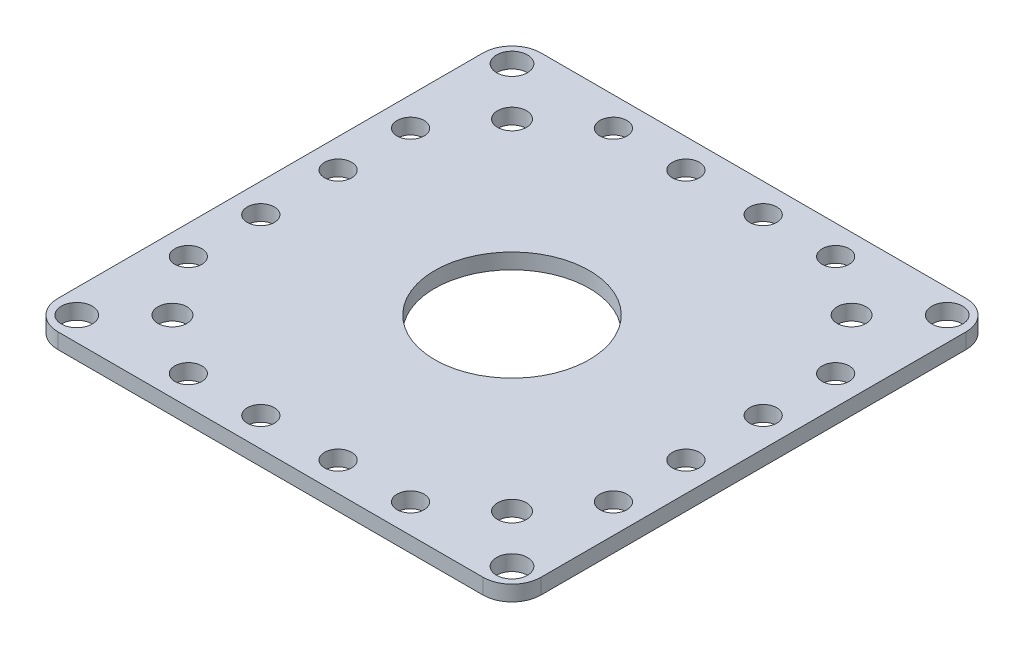
SolidWorks part; units mm, degrees
ref_plane "Front Plane" through (0, 0, 0) normal (0, 0, 1) x (1, 0, 0)
ref_plane "Top Plane" through (0, 0, 0) normal (0, 1, 0) x (1, 0, 0)
ref_plane "Right Plane" through (0, 0, 0) normal (1, 0, 0) x (0, 0, -1)
sketch "Sketch1" plane through (0, 0, 0) normal (0, 1, 0) x (1, 0, 0)
  line L0 (0, 25) -> (0, -25) construction
  line L1 (-25, -25) -> (25, -25)
  line L2 (-25, -25) -> (-25, 25)
  line L3 (-25, 25) -> (25, 25)
  line L4 (25, -25) -> (25, 25)
  line L5 (-25, -25) -> (25, 25) construction
  line L6 (-25, 25) -> (25, -25) construction
  circle A0 centre (0, 0) radius 8
  circle A1 centre (-22.5251, 22.5251) radius 1.6
  circle A2 centre (-17.5754, 17.5754) radius 1.5
  circle A3 centre (-4, 22) radius 1.4
  circle A4 centre (-11.5, 22) radius 1.4
  circle A5 centre (4, 22) radius 1.4
  circle A6 centre (11.5, 22) radius 1.4
  circle A7 centre (22, 11.5) radius 1.4
  circle A8 centre (22, 4) radius 1.4
  circle A9 centre (22, -4) radius 1.4
  circle A10 centre (22, -11.5) radius 1.4
  circle A11 centre (11.5, -22) radius 1.4
  circle A12 centre (4, -22) radius 1.4
  circle A13 centre (-4, -22) radius 1.4
  circle A14 centre (-11.5, -22) radius 1.4
  circle A15 centre (-22, -11.5) radius 1.4
  circle A16 centre (-22, -4) radius 1.4
  circle A17 centre (-22, 4) radius 1.4
  circle A18 centre (-22, 11.5) radius 1.4
  circle A19 centre (22.5251, 22.5251) radius 1.6
  circle A20 centre (17.5754, 17.5754) radius 1.5
  circle A21 centre (22.5251, -22.5251) radius 1.6
  circle A22 centre (17.5754, -17.5754) radius 1.5
  circle A23 centre (-22.5251, -22.5251) radius 1.6
  circle A24 centre (-17.5754, -17.5754) radius 1.5
  point P0 (0, 0)
  point P49 (0, 0)
  point P62 (0, 0)
  dimension "D2" = 16
  dimension "D3" = 3.2
  dimension "D4" = 3
  dimension "D6" = 2.8
  dimension "D8" = 2.8
  dimension "D1" = 50
  dimension "D5" = 3
  dimension "D7" = 4
  dimension "D9" = 7.5
  dimension "D11" = 7
  dimension "D12" = 3.5
  dimension "D10" = 4
  dimension "D13" = 4
extrude "Boss-Extrude1" add sketch "Sketch1" along normal blind 1.6
fillet "Fillet1" radius 3 4 edges at (25, 0.8, 25) (-25, 0.8, 25) (25, 0.8, -25) (-25, 0.8, -25)
